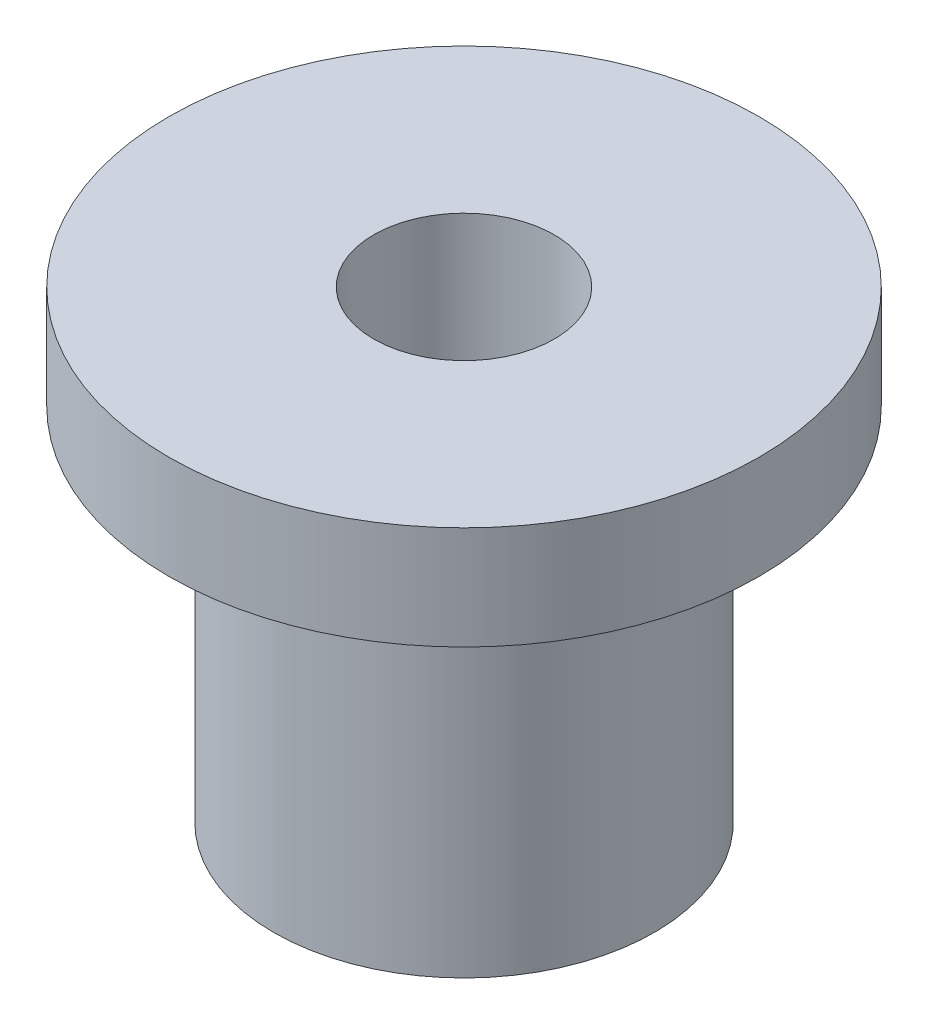
SolidWorks part; units mm, degrees
ref_plane "Front Plane" through (0, 0, 0) normal (0, 0, 1) x (1, 0, 0)
ref_plane "Top Plane" through (0, 0, 0) normal (0, 1, 0) x (1, 0, 0)
ref_plane "Right Plane" through (0, 0, 0) normal (1, 0, 0) x (0, 0, -1)
sketch "Sketch1" plane through (0, 0, 0) normal (0, 1, 0) x (1, 0, 0)
  circle A0 centre (0, 0) radius 3.687
  circle A1 centre (0, 0) radius 1.75
  dimension "D1" = 7.374
  dimension "D2" = 3.5
extrude "Boss-Extrude1" add sketch "Sketch1" along normal blind 6.985
sketch "Sketch2" plane through (0, 6.985, 0) normal (0, 1, 0) x (1, 0, 0)
  circle A0 centre (0, 0) radius 1.75 construction
  circle A1 centre (0, 0) radius 1.75
  circle A2 centre (0, 0) radius 5.715
  dimension "D1" = 11.43
extrude "Boss-Extrude2" add sketch "Sketch2" along normal blind 2
fillet "Fillet1" radius 0.5 1 edges at (0, 6.985, 3.687)
